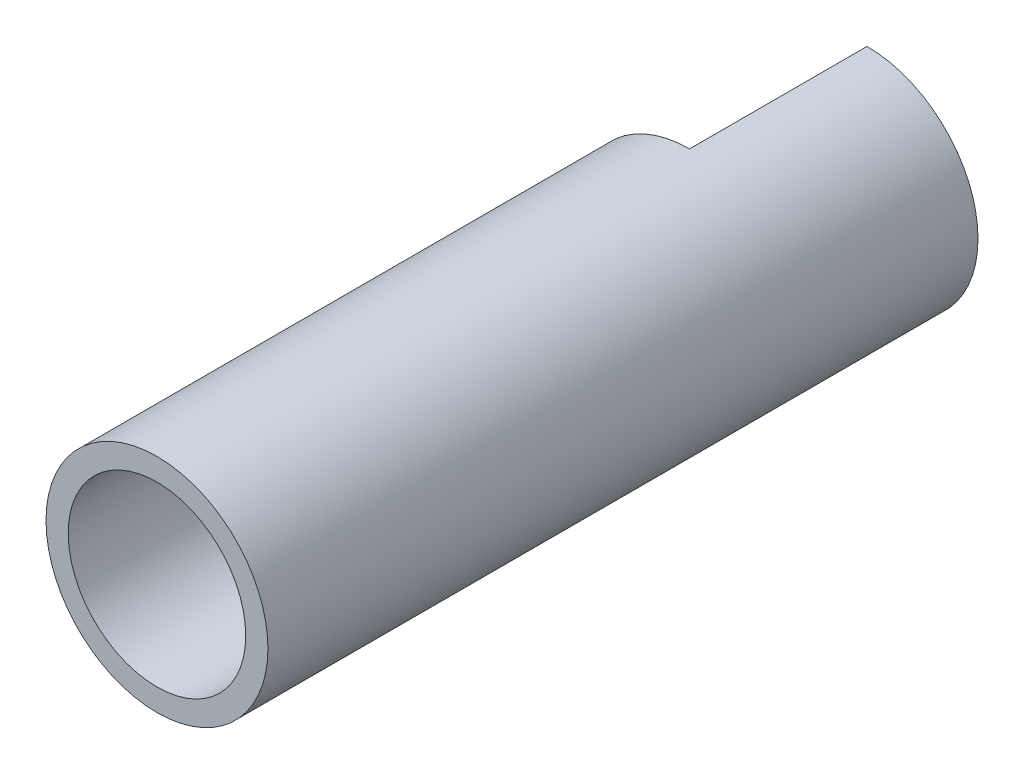
SolidWorks part; units mm, degrees
ref_plane "Front Plane" through (0, 0, 0) normal (0, 0, 1) x (1, 0, 0)
ref_plane "Top Plane" through (0, 0, 0) normal (0, 1, 0) x (1, 0, 0)
ref_plane "Right Plane" through (0, 0, 0) normal (1, 0, 0) x (0, 0, -1)
sketch "Sketch1" plane through (0, 0, 0) normal (0, 0, 1) x (1, 0, 0)
  circle A0 centre (0, 0) radius 25.4
  circle A1 centre (0, 0) radius 31.75
  dimension "D1" = 50.8
  dimension "D2" = 63.5
extrude "Boss-Extrude1" add sketch "Sketch1" along normal blind 203.2
sketch "Sketch2" plane through (0, 0, 0) normal (1, 0, 0) x (0, 0, -1)
  line L0 (-203.2, -31.75) -> (0, -31.75) construction
  line L1 (0, 31.75) -> (-50.8, 31.75)
  line L2 (0, 31.75) -> (0, -31.75)
  line L3 (0, -31.75) -> (-50.8, -31.75)
  line L4 (-50.8, 31.75) -> (-50.8, -31.75)
  dimension "D1" = 50.8
extrude "Cut-Extrude1" cut sketch "Sketch2" against normal up to next
